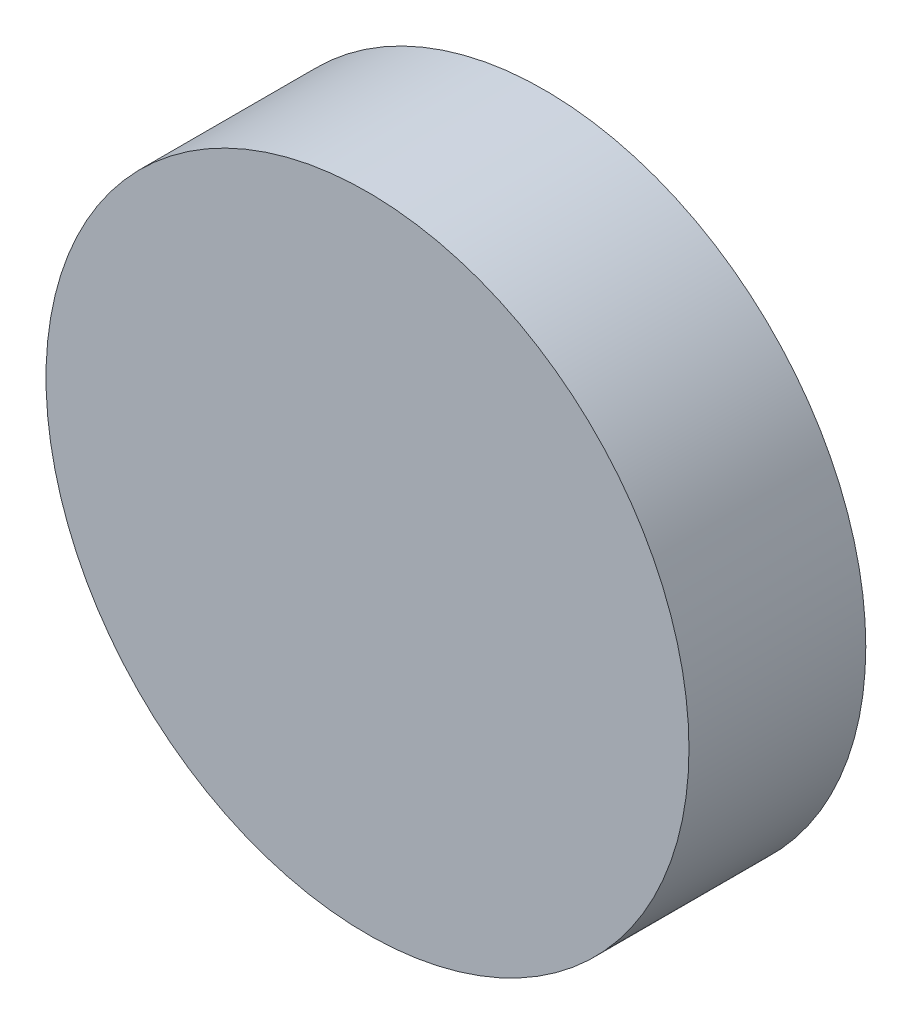
SolidWorks part; units mm, degrees
material "ABS PC"
ref_plane "Front Plane" through (0, 0, 0) normal (0, 0, 1) x (1, 0, 0)
ref_plane "Top Plane" through (0, 0, 0) normal (0, 1, 0) x (1, 0, 0)
ref_plane "Right Plane" through (0, 0, 0) normal (1, 0, 0) x (0, 0, -1)
sketch "Extrude sketch 1" plane through (0, 0, 0) normal (0, 0, 1) x (1, 0, 0)
  circle A0 centre (860, 225) radius 40
  dimension "D1" = 80
extrude "Extrude 1" add sketch "Extrude sketch 1" along normal blind 22 from offset 800 separate body
